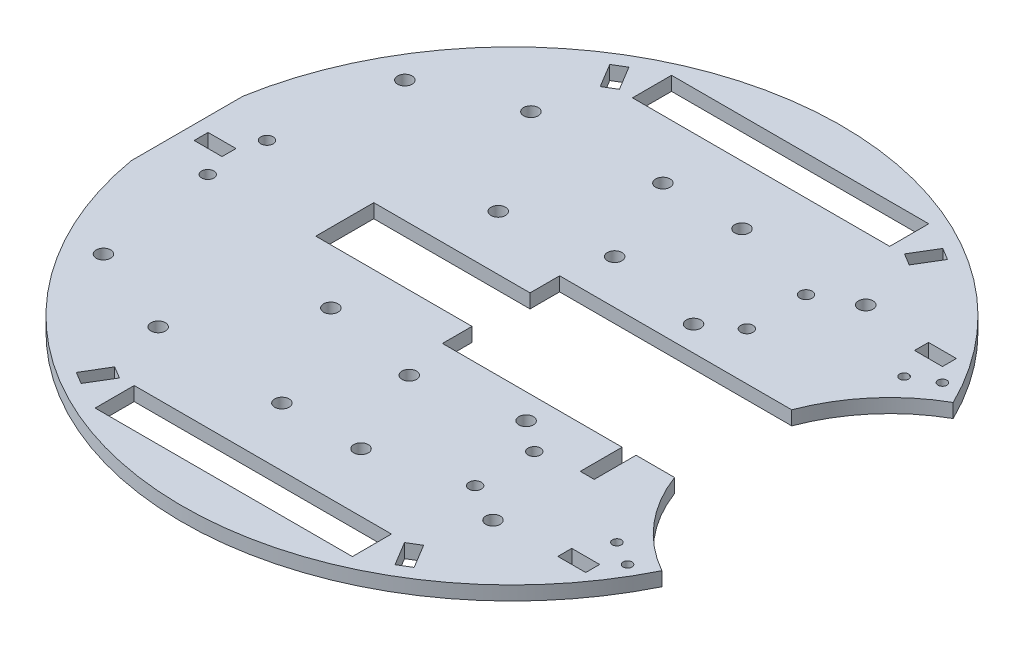
SolidWorks part; units mm, degrees
material "Acrylic (Medium-high impact)"
ref_plane "Front Plane" through (0, 0, 0) normal (0, 0, 1) x (1, 0, 0)
ref_plane "Top Plane" through (0, 0, 0) normal (0, 1, 0) x (1, 0, 0)
ref_plane "Right Plane" through (0, 0, 0) normal (1, 0, 0) x (0, 0, -1)
sketch "Sketch1" plane through (0, 0, 0) normal (0, 1, 0) x (1, 0, 0)
  line L0 (67.2709, 33.1606) -> (86.0323, 0) construction
  line L1 (86.0323, 0) -> (67.2709, -33.1606) construction
  line L2 (0, 65.5895) -> (0, 75) construction
  line L3 (-29.2721, -56.6995) -> (29.2721, -56.6995)
  line L4 (-29.2721, -56.6995) -> (-29.2721, -65.5895)
  line L5 (-29.2721, -65.5895) -> (29.2721, -65.5895)
  line L6 (29.2721, -56.6995) -> (29.2721, -65.5895)
  line L7 (-29.2721, 65.5895) -> (29.2721, 65.5895)
  line L8 (-29.2721, 65.5895) -> (-29.2721, 56.6995)
  line L9 (-29.2721, 56.6995) -> (29.2721, 56.6995)
  line L10 (29.2721, 65.5895) -> (29.2721, 56.6995)
  line L11 (29.2721, 65.5895) -> (30.566, 68.4888) construction
  line L12 (29.2721, -65.5895) -> (30.566, -68.4888) construction
  line L13 (-62.4869, 6.731) -> (-62.4869, -6.731) construction
  line L14 (-62.4869, 0) -> (-73.9169, 0) construction
  line L16 (58.9661, -42.1806) -> (52.6161, -42.1806)
  line L17 (58.9661, -42.1806) -> (58.9661, -39.0056)
  line L18 (58.9661, -39.0056) -> (52.6161, -39.0056)
  line L19 (52.6161, -42.1806) -> (52.6161, -39.0056)
  line L20 (58.9661, 42.1806) -> (52.6161, 42.1806)
  line L21 (58.9661, 42.1806) -> (58.9661, 39.0056)
  line L22 (60.7114, 44.0354) -> (67.2709, 33.1606) construction
  line L23 (0, 0) -> (86.0323, 0) construction
  line L24 (52.6161, 42.1806) -> (52.6161, 39.0056)
  line L25 (58.9661, 39.0056) -> (52.6161, 39.0056)
  line L28 (-38.1, -42.418) -> (0, -23.368) construction
  line L29 (0, -23.368) -> (38.1, -42.418) construction
  line L30 (-38.1, -42.418) -> (38.1, -42.418) construction
  line L31 (0, -23.368) -> (0, -42.418) construction
  line L32 (-2.4867, 6.604) -> (-2.4867, 13.335) construction
  line L33 (38.4073, -13.335) -> (-2.4867, -13.335) construction
  line L34 (-2.4867, -13.335) -> (-2.4867, -6.604) construction
  line L35 (-2.4867, 13.335) -> (38.4073, 13.335) construction
  line L36 (38.4073, 13.335) -> (41.5823, 13.335)
  line L37 (32.441, -56.8953) -> (35.7191, -62.3337)
  line L38 (32.441, -56.8953) -> (35.1602, -55.2563)
  line L39 (35.7191, -62.3337) -> (38.4383, -60.6947)
  line L40 (35.1602, -55.2563) -> (38.4383, -60.6947)
  line L41 (-58.6769, -34.29) -> (-58.6769, 34.29) construction
  line L42 (0, 0) -> (-16.51, 0) construction
  line L43 (-58.6769, 0) -> (-62.4869, 0) construction
  line L44 (41.5823, 13.335) -> (50.3421, 13.335)
  line L45 (41.5823, -13.335) -> (46.2813, -13.335)
  line L46 (-2.4867, -6.604) -> (-2.4867, -13.335)
  line L47 (-73.9169, 12.7) -> (-73.9169, -12.7)
  line L48 (38.4073, 13.335) -> (-2.4867, 13.335)
  line L49 (-2.4867, 13.335) -> (-2.4867, 6.604)
  line L50 (-2.4867, -13.335) -> (38.4073, -13.335)
  line L51 (46.2813, -13.335) -> (50.3421, -13.335)
  line L52 (-2.4867, 0) -> (-38.0467, 0) construction
  line L53 (-2.4867, 6.604) -> (-38.0467, 6.604)
  line L54 (14.856, 13.335) -> (14.856, 0) construction
  line L55 (-2.4867, -6.604) -> (-38.0467, -6.604)
  line L56 (-38.0467, 6.604) -> (-38.0467, -6.604)
  line L57 (14.856, 0) -> (14.856, -13.335) construction
  line L58 (32.441, -56.8953) -> (38.4383, -60.6947) construction
  line L59 (35.7191, -62.3337) -> (35.1602, -55.2563) construction
  line L60 (41.5823, -13.335) -> (41.5823, -22.86)
  line L61 (41.5823, -22.86) -> (38.4073, -22.86)
  line L62 (38.4073, -13.335) -> (38.4073, -22.86)
  line L63 (33.8006, -56.0758) -> (0, 0) construction
  line L64 (37.0787, -61.5142) -> (38.7178, -64.2334) construction
  line L65 (-32.441, -56.8953) -> (-35.1602, -55.2563)
  line L66 (-32.441, -56.8953) -> (-35.7191, -62.3337)
  line L67 (-35.7191, -62.3337) -> (-38.4383, -60.6947)
  line L68 (-35.1602, -55.2563) -> (-38.4383, -60.6947)
  line L69 (-35.1602, 55.2563) -> (-38.4383, 60.6947)
  line L70 (-32.441, 56.8953) -> (-35.1602, 55.2563)
  line L71 (-32.441, 56.8953) -> (-35.7191, 62.3337)
  line L72 (-35.7191, 62.3337) -> (-38.4383, 60.6947)
  line L73 (35.1602, 55.2563) -> (38.4383, 60.6947)
  line L74 (32.441, 56.8953) -> (35.1602, 55.2563)
  line L75 (32.441, 56.8953) -> (35.7191, 62.3337)
  line L76 (35.7191, 62.3337) -> (38.4383, 60.6947)
  line L77 (-73.9169, 0) -> (-70.7419, 0) construction
  line L78 (-70.7419, 1.5875) -> (-64.3919, 1.5875)
  line L79 (-70.7419, 1.5875) -> (-70.7419, -1.5875)
  line L80 (-70.7419, -1.5875) -> (-64.3919, -1.5875)
  line L81 (-64.3919, 1.5875) -> (-64.3919, -1.5875)
  arc A0 (67.2709, 33.1606) -> (-73.9169, 12.7) centre (0, 0) ccw
  arc A1 (67.2709, -33.1606) -> (55.0862, -22.225) centre (86.0323, 0) cw
  circle A2 centre (-62.4869, 6.731) radius 1.397
  circle A3 centre (-62.4869, -6.731) radius 1.397
  circle A4 centre (-38.1, -42.418) radius 1.651
  circle A5 centre (38.1, -42.418) radius 1.651
  circle A6 centre (38.1, 42.418) radius 1.651
  circle A7 centre (0, -23.368) radius 1.651
  circle A8 centre (-38.1, 42.418) radius 1.651
  circle A9 centre (0, 23.368) radius 1.651
  circle A10 centre (29.2721, -37.6495) radius 1.397
  arc A11 (55.0862, -22.225) -> (50.3421, -13.335) centre (86.0323, 0) cw
  circle A12 centre (-58.6769, 34.29) radius 1.651
  circle A13 centre (62.1411, -35.8306) radius 1.016
  circle A14 centre (56.5708, -32.6791) radius 1.016
  circle A15 centre (-58.6769, -34.29) radius 1.651
  arc A16 (50.3421, 13.335) -> (67.2709, 33.1606) centre (86.0323, 0) cw
  arc A17 (-73.9169, -12.7) -> (67.2709, -33.1606) centre (0, 0) ccw
  circle A18 centre (29.2721, -24.1875) radius 1.397
  circle A19 centre (29.2721, 37.6495) radius 1.397
  circle A20 centre (29.2721, 24.1875) radius 1.397
  circle A21 centre (8.9992, -43.3535) radius 1.651
  circle A22 centre (-9.0008, -43.3535) radius 1.651
  circle A23 centre (-9.0008, 43.3535) radius 1.651
  circle A24 centre (8.9992, 43.3535) radius 1.651
  circle A25 centre (62.1411, 35.8306) radius 1.016
  circle A26 centre (56.5708, 32.6791) radius 1.016
  circle A27 centre (56.5708, 32.6791) radius 1.016 construction
  circle A28 centre (22.2783, 19.05) radius 1.651
  circle A29 centre (22.2783, -19.05) radius 1.651
  circle A30 centre (-22.1717, -19.05) radius 1.651
  circle A31 centre (-22.1717, 19.05) radius 1.651
  circle A32 centre (22.2783, 19.05) radius 1.651 construction
  point P50 (41.5823, 0)
  point P56 (47.9323, 0)
  point P63 (35.4397, -58.795)
  dimension "D1" = 150
  dimension "D7" = 11.43
  dimension "D8" = 2.794
  dimension "D14" = 76.2
  dimension "D16" = 3.302
  dimension "D22" = 13.208
  dimension "D27" = 3.302
  dimension "D34" = 2.794
  dimension "D36" = 19.05
  dimension "D2" = 121
  dimension "D3" = 38.1
  dimension "D4" = 58.5441
  dimension "D5" = 8.89
  dimension "D6" = 3.175
  dimension "D9" = 13.462
  dimension "D10" = 6.35
  dimension "D11" = 3.175
  dimension "D12" = 3.175
  dimension "D13" = 3.175
  dimension "D15" = 3.175
  dimension "D17" = 42.418
  dimension "D18" = 25.4
  dimension "D19" = 26.67
  dimension "D20" = 44.069
  dimension "D21" = 17.3428
  dimension "D23" = 38.1
  dimension "D24" = 9.525
  dimension "D25" = 15.24
  dimension "D26" = 68.58
  dimension "D28" = 44.45
  dimension "D29" = 35.56
  dimension "D30" = 6.35
  dimension "D31" = 88.519
  dimension "D32" = 16.51
  dimension "D33" = 13.462
  dimension "D35" = 19.05
  dimension "D37" = 3.175
  dimension "D38" = 3.175
  dimension "D39" = 3.175
extrude "Boss-Extrude1" add sketch "Sketch1" along normal blind 3.175
equation "\"Diameter\"= 2.75"
equation "\"D4@Sketch1\"=\"Diameter\"*sin(arccos(1-(5/(4*\"Diameter\"))))"
